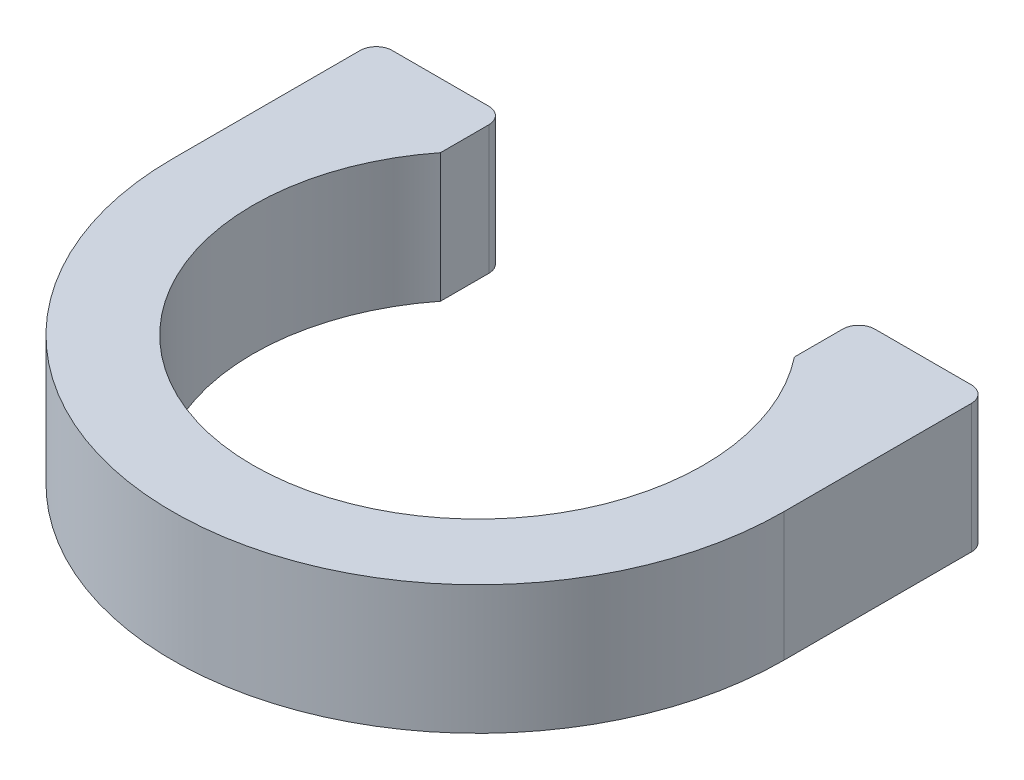
SolidWorks part; units mm, degrees
ref_plane "Front Plane" through (0, 0, 0) normal (0, 0, 1) x (1, 0, 0)
ref_plane "Top Plane" through (0, 0, 0) normal (0, 1, 0) x (1, 0, 0)
ref_plane "Right Plane" through (0, 0, 0) normal (1, 0, 0) x (0, 0, -1)
sketch "Sketch1" plane through (0, 0, 0) normal (0, 1, 0) x (1, 0, 0)
  line L0 (-6, 7.9151) -> (-9, 7.9151)
  line L1 (-5.5, 7.4151) -> (-5.5, 5.9151)
  line L2 (-9.5, 7.4151) -> (-9.5, 1.5849)
  line L3 (6, 7.9151) -> (9, 7.9151)
  line L4 (5.5, 7.4151) -> (5.5, 5.9151)
  line L5 (9.5, 1.5849) -> (9.5, 7.4151)
  arc A0 (-7, 1.5849) -> (7, 1.5849) centre (0, 1.5849) ccw
  arc A1 (-9.5, 1.5849) -> (9.5, 1.5849) centre (0, 1.5849) ccw
  arc A2 (-9.5, 7.4151) -> (-9, 7.9151) centre (-9, 7.4151) cw
  arc A3 (9, 7.9151) -> (9.5, 7.4151) centre (9, 7.4151) cw
  arc A4 (-5.5, 5.9151) -> (5.5, 5.9151) centre (0, 1.5849) ccw
  arc A5 (6, 7.9151) -> (5.5, 7.4151) centre (6, 7.4151) ccw
  arc A6 (-6, 7.9151) -> (-5.5, 7.4151) centre (-6, 7.4151) cw
  dimension "D1" = 0.5
extrude "Boss-Extrude1" add sketch "Sketch1" along normal blind 4 contours A6 L0 A2 L2 A1 L5 A3 L3 A5 L4 A4 A0 L1
